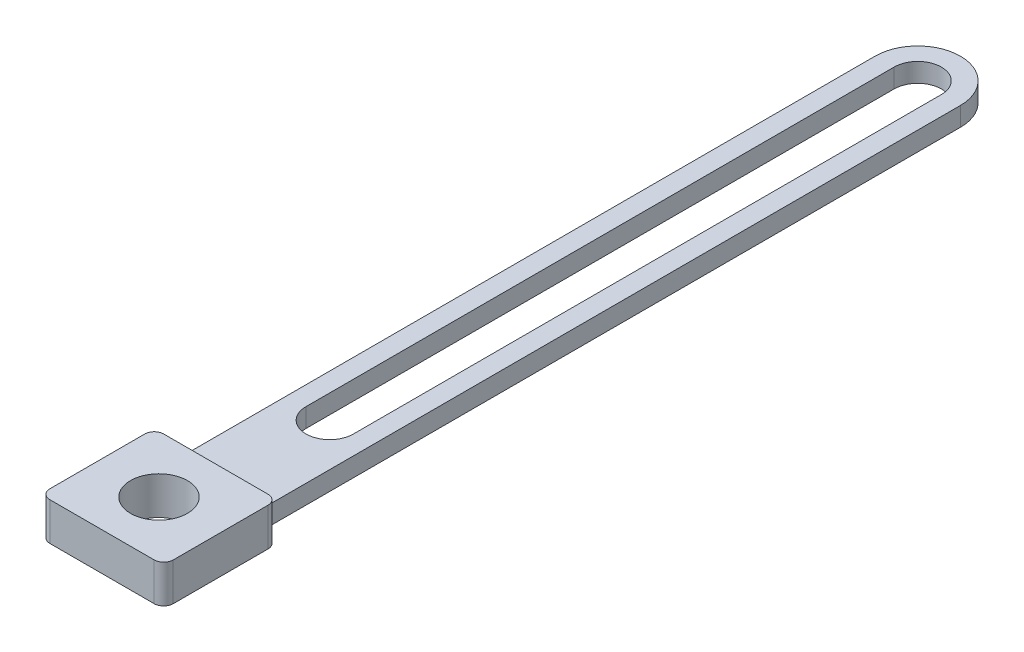
SolidWorks part; units mm, degrees
ref_plane "Front Plane" through (0, 0, 0) normal (0, 0, 1) x (1, 0, 0)
ref_plane "Top Plane" through (0, 0, 0) normal (0, 1, 0) x (1, 0, 0)
ref_plane "Right Plane" through (0, 0, 0) normal (1, 0, 0) x (0, 0, -1)
sketch "Sketch1" plane through (0, 0, 0) normal (0, 1, 0) x (1, 0, 0)
  line L2 (-7.3816, 14.9605) -> (-7.3816, -65.0395)
  line L4 (1.6184, 14.9605) -> (1.6184, -65.0395)
  arc A0 (-7.3816, 14.9605) -> (1.6184, 14.9605) centre (-2.8816, 14.9605) cw
  arc A1 (-7.3816, -65.0395) -> (1.6184, -65.0395) centre (-2.8816, -65.0395) ccw
  dimension "D1" = 9
  dimension "D2" = 80
extrude "Boss-Extrude1" add sketch "Sketch1" along normal mid plane 2
sketch "Sketch2" plane through (0, 1, 0) normal (0, 1, 0) x (1, 0, 0)
  line L0 (-5.3816, 14.9605) -> (-5.3816, -47.0395)
  line L1 (-0.3816, 14.9605) -> (-0.3816, -47.0395)
  arc A1 (-0.3816, 14.9605) -> (-5.3816, 14.9605) centre (-2.8816, 14.9605) ccw
  arc A6 (-5.3816, -47.0395) -> (-0.3816, -47.0395) centre (-2.8816, -47.0395) ccw
  dimension "D3" = 5
  dimension "D4" = 5
  dimension "D1" = 62
extrude "Cut-Extrude1" cut sketch "Sketch2" against normal blind 2
sketch "Sketch3" plane through (0, 1, 0) normal (0, 1, 0) x (1, 0, 0)
  line L0 (-7.3816, 14.9605) -> (-7.3816, -65.0395) construction
  line L1 (-9.3816, -59.0395) -> (3.6184, -59.0395)
  line L2 (-9.3816, -59.0395) -> (-9.3816, -71.0395)
  line L3 (-9.3816, -71.0395) -> (3.6184, -71.0395)
  line L4 (3.6184, -59.0395) -> (3.6184, -71.0395)
  line L5 (1.6184, -65.0395) -> (1.6184, 14.9605) construction
  arc A0 (-7.3816, -65.0395) -> (1.6184, -65.0395) centre (-2.8816, -65.0395) ccw construction
  dimension "D1" = 2
  dimension "D2" = 2
  dimension "D3" = 13
  dimension "D4" = 12
  dimension "D5" = 6
extrude "Boss-Extrude2" add sketch "Sketch3" along normal mid plane 4
fillet "Fillet1" radius 1 4 edges at (-9.3816, 1, 59.0395) (3.6184, 1, 59.0395) (3.6184, 1, 71.0395) (-9.3816, 1, 71.0395)
sketch "Sketch4" plane through (0, 3, 0) normal (0, 1, 0) x (1, 0, 0)
  line L0 (-8.3816, -71.0395) -> (2.6184, -71.0395) construction
  line L1 (-9.3816, -60.0395) -> (-9.3816, -70.0395) construction
  circle A0 centre (-2.8816, -65.0395) radius 3
  dimension "D1" = 6
  dimension "D2" = 6
  dimension "D3" = 6.5
extrude "Cut-Extrude2" cut sketch "Sketch4" against normal blind 4
